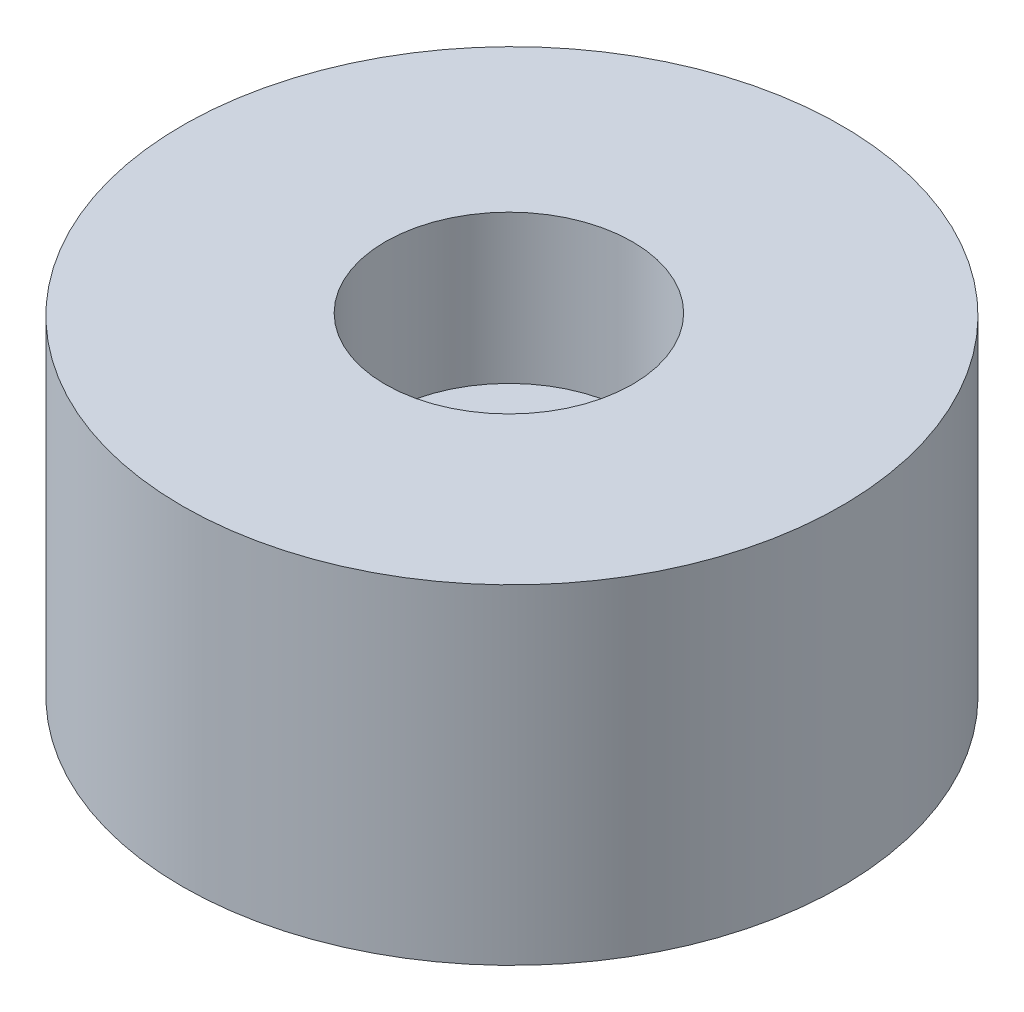
SolidWorks part; units mm, degrees
ref_plane "Front" through (0, 0, 0) normal (0, 0, 1) x (1, 0, 0)
ref_plane "Top" through (0, 0, 0) normal (0, 1, 0) x (1, 0, 0)
ref_plane "Right" through (0, 0, 0) normal (1, 0, 0) x (0, 0, -1)
sketch "Sketch1" plane through (0, 0, 0) normal (0, 1, 0) x (1, 0, 0)
  circle A0 centre (-17.2787, 9.1647) radius 20
extrude "Boss-Extrude3" add sketch "Sketch1" along normal blind 20
sketch "Sketch4" plane through (0, 20, 0) normal (0, 1, 0) x (1, 0, 0)
  circle A0 centre (-17.5134, 9.215) radius 7.5
extrude "Cut-Extrude1" cut sketch "Sketch4" against normal blind 9
